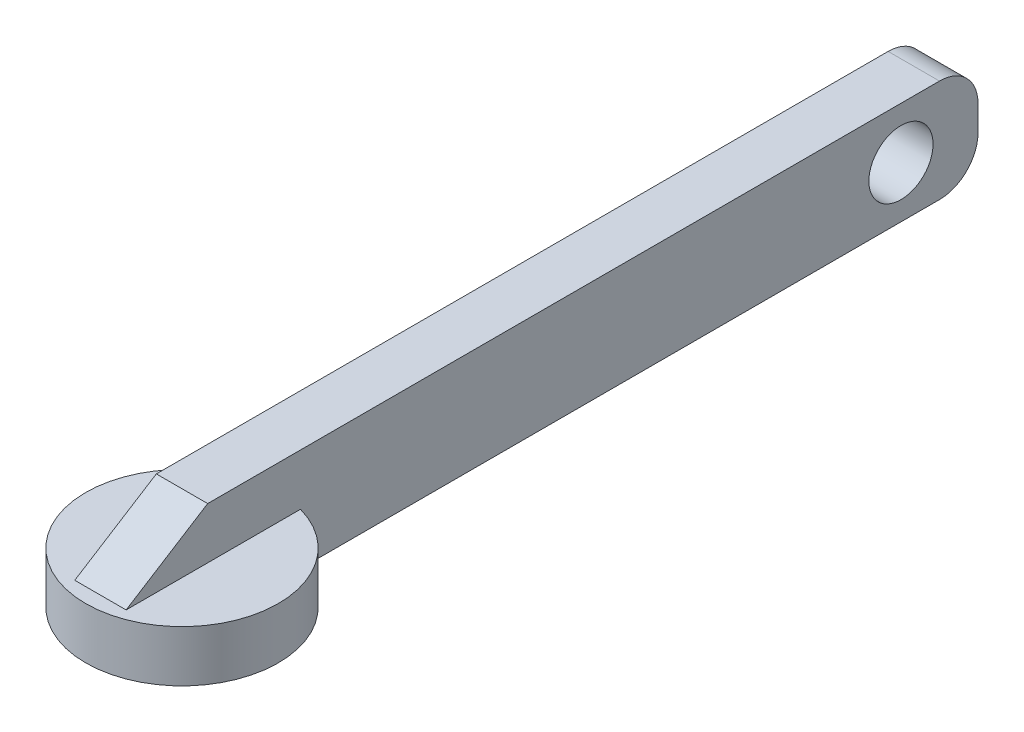
SolidWorks part; units mm, degrees
ref_plane "Front Plane" through (0, 0, 0) normal (0, 0, 1) x (1, 0, 0)
ref_plane "Top Plane" through (0, 0, 0) normal (0, 1, 0) x (1, 0, 0)
ref_plane "Right Plane" through (0, 0, 0) normal (1, 0, 0) x (0, 0, -1)
sketch "Sketch1" plane through (0, 0, 0) normal (0, 1, 0) x (1, 0, 0)
  line L1 (-2, -30) -> (2, -30)
  line L2 (-2, -30) -> (-2, 30)
  line L3 (-2, 30) -> (2, 30)
  line L4 (2, -30) -> (2, 30)
  line L5 (-2, -30) -> (2, 30) construction
  line L6 (-2, 30) -> (2, -30) construction
  point P0 (0, 0)
  dimension "D1" = 4
  dimension "D2" = 60
extrude "Boss-Extrude1" add sketch "Sketch1" along normal blind 8
sketch "Sketch2" plane through (-2, 0, 0) normal (-1, 0, 0) x (0, 0, 1)
  line L0 (-30, 8) -> (-30, 0) construction
  circle A0 centre (-24, 4) radius 2.5
  dimension "D1" = 5
  dimension "D2" = 6
extrude "Cut-Extrude1" cut sketch "Sketch2" against normal blind 8
fillet "Fillet1" radius 3 2 edges at (0, 8, -30) (0, 0, -30)
sketch "Sketch3" plane through (0, 0, 0) normal (0, -1, 0) x (1, 0, 0)
  line L0 (-2, 30) -> (2, 30) construction
  circle A0 centre (0, 30) radius 7.5
  dimension "D1" = 15
extrude "Boss-Extrude2" add sketch "Sketch3" against normal blind 4
sketch "Sketch4" plane through (2, 0, 0) normal (1, 0, 0) x (0, 0, -1)
  line L0 (-30, 4) -> (-36.3517, 4)
  line L1 (-36.3517, 4) -> (-30, 8)
  line L2 (-30, 8) -> (-30, 4)
extrude "Boss-Extrude3" add sketch "Sketch4" against normal blind 4
